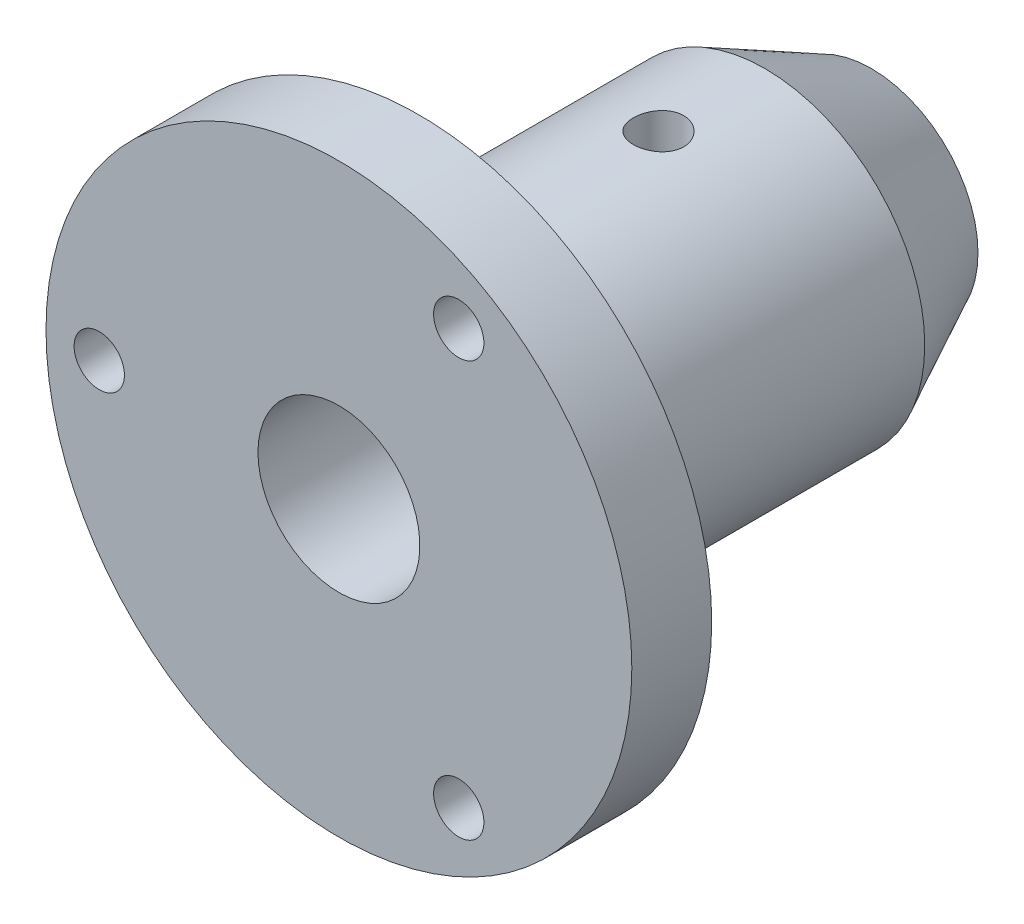
SolidWorks part; units mm, degrees
ref_plane "Front Plane" through (0, 0, 0) normal (0, 0, 1) x (1, 0, 0)
ref_plane "Top Plane" through (0, 0, 0) normal (0, 1, 0) x (1, 0, 0)
ref_plane "Right Plane" through (0, 0, 0) normal (1, 0, 0) x (0, 0, -1)
sketch "Sketch1" plane through (0, 0, 0) normal (0, 0, 1) x (1, 0, 0)
  circle A0 centre (0, 0) radius 9.525
  dimension "D1" = 19.05
extrude "Boss-Extrude1" add sketch "Sketch1" along normal blind 31.75
sketch "Sketch18" plane through (0, 0, 31.75) normal (0, 0, 1) x (1, 0, 0)
  circle A0 centre (0, 0) radius 17.4625
  dimension "D1" = 34.925
extrude "Boss-Extrude2" add sketch "Sketch18" against normal blind 4.7625
sketch "Sketch12" plane through (0, 0, 0) normal (0, 0, -1) x (-1, 0, 0)
  circle A0 centre (0, 0) radius 4.826
  dimension "D1" = 9.652
extrude "Cut-Extrude3" cut sketch "Sketch12" against normal blind 31.75
sketch "Sketch14" plane through (0, 0, 0) normal (0, 1, 0) x (1, 0, 0)
  line L0 (9.525, 0) -> (-9.525, 0) construction
  circle A0 centre (0, -12.7) radius 1.5
  circle A1 centre (0, -22.225) radius 1.5
  dimension "D1" = 3
  dimension "D2" = 3
  dimension "D3" = 9.525
  dimension "D4" = 12.7
extrude "Cut-Extrude4" cut sketch "Sketch14" against normal through all and the other way through all
sketch "Sketch17" plane through (0, 0, 31.75) normal (0, 0, 1) x (1, 0, 0)
  line L0 (0, 0) -> (7.1438, 12.3733) construction
  line L1 (0, 0) -> (0, 3.3204) construction
  circle A0 centre (7.1438, 12.3733) radius 1.5
  circle A1 centre (0, 0) radius 14.2875 construction
  dimension "D1" = 3
  dimension "D2" = 14.2875
  dimension "D3" = 30
extrude "Cut-Extrude5" cut sketch "Sketch17" against normal blind 6.35
pattern_circular "CirPattern1" count 3 over 360 about axis through (0, 0, 0) along (0, 0, 1) of "Cut-Extrude5"
sketch "Sketch16" plane through (0, 0, 0) normal (0, 1, 0) x (1, 0, 0)
  line L0 (-6.35, 0) -> (-9.525, -6.35)
  line L1 (9.525, 0) -> (-9.525, 0) construction
  line L2 (-9.525, -6.35) -> (-9.525, 0)
  line L3 (-9.525, 0) -> (-6.35, 0)
  line L4 (0, 0) -> (0, -30.8644) construction
  line L5 (-9.525, 0) -> (-9.525, -26.9875) construction
  dimension "D1" = 12.7
  dimension "D2" = 6.35
revolve "Cut-Revolve1" cut sketch "Sketch16" angle 360 about L4
sketch "Sketch19" plane through (0, 0, 26.9875) normal (0, 0, -1) x (-1, 0, 0)
  circle A0 centre (-7.1438, 12.3733) radius 2.75
  dimension "D1" = 5.5
fillet "Fillet1" radius 1.5875 1 edges at (9.525, 0, 26.9875)
